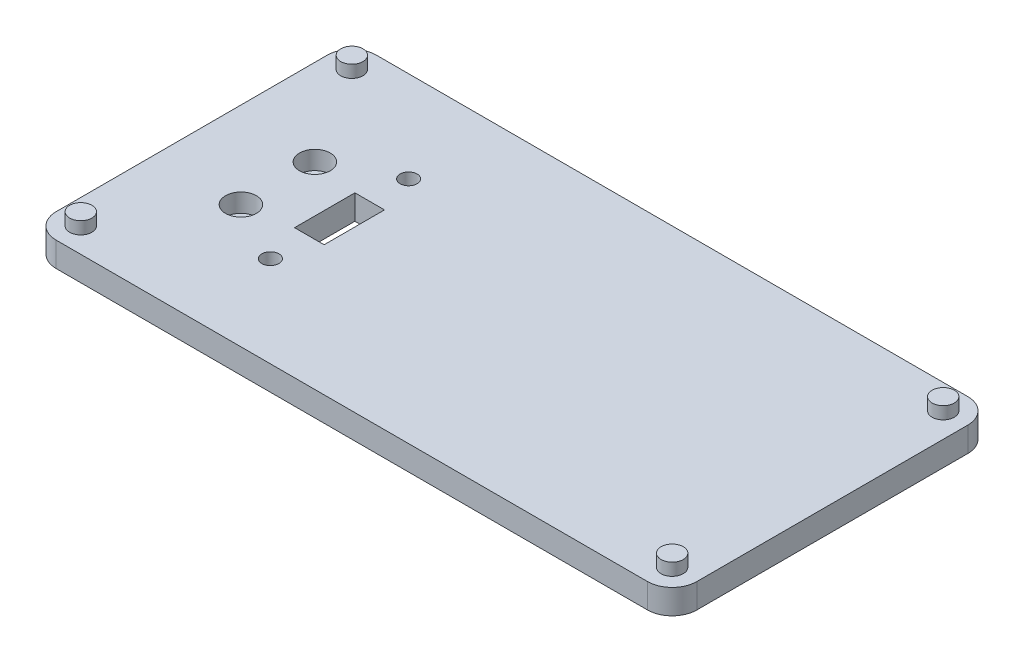
SolidWorks part; units mm, degrees
ref_plane "Front Plane" through (0, 0, 0) normal (0, 0, 1) x (1, 0, 0)
ref_plane "Top Plane" through (0, 0, 0) normal (0, 1, 0) x (1, 0, 0)
ref_plane "Right Plane" through (0, 0, 0) normal (1, 0, 0) x (0, 0, -1)
sketch "Sketch1" plane through (0, 0, 0) normal (0, 1, 0) x (1, 0, 0)
  line L1 (0, 0) -> (121.92, 0)
  line L2 (0, 0) -> (0, 66.04)
  line L3 (0, 66.04) -> (121.92, 66.04)
  line L4 (121.92, 0) -> (121.92, 66.04)
  dimension "D1" = 121.92
  dimension "D2" = 66.04
extrude "Boss-Extrude1" add sketch "Sketch1" along normal blind 5.08
fillet "Fillet1" radius 5.08 4 edges at (0, 2.54, -66.04) (121.92, 2.54, -66.04) (121.92, 2.54, 0) (0, 2.54, 0)
sketch "Sketch2" plane through (0, 5.08, 0) normal (0, 1, 0) x (1, 0, 0)
  line L0 (30.48, 39.243) -> (30.48, 26.797) construction
  line L1 (27.432, 39.243) -> (33.528, 39.243)
  line L2 (27.432, 39.243) -> (27.432, 26.797)
  line L3 (27.432, 26.797) -> (33.528, 26.797)
  line L4 (33.528, 39.243) -> (33.528, 26.797)
  line L5 (0, 60.96) -> (0, 5.08) construction
  line L6 (27.432, 33.02) -> (33.528, 33.02) construction
  circle A2 centre (30.48, 47.2694) radius 1.7526
  circle A3 centre (30.48, 18.7706) radius 1.7526
  dimension "D4" = 14.2494
  dimension "D2" = 3.5052
  dimension "D1" = 6.096
  dimension "D3" = 12.446
  dimension "D5" = 27.94
  dimension "D6" = 30.48
sketch "Sketch3" plane through (0, 5.08, 0) normal (0, 1, 0) x (1, 0, 0)
  line L0 (116.84, 66.04) -> (5.08, 66.04) construction
  line L1 (5.08, 0) -> (116.84, 0) construction
  line L2 (0, 60.96) -> (0, 5.08) construction
  circle A0 centre (17.78, 40.64) radius 3.175
  circle A1 centre (17.78, 25.4) radius 3.175
  dimension "D1" = 6.35
  dimension "D2" = 6.35
  dimension "D3" = 25.4
  dimension "D4" = 25.4
  dimension "D5" = 17.78
extrude "Cut-Extrude2" cut sketch "Sketch2" against normal up to next
extrude "Cut-Extrude3" cut sketch "Sketch3" against normal blind 3.81
sketch "Sketch4" plane through (0, 1.27, 0) normal (0, 1, 0) x (1, 0, 0)
  circle A0 centre (17.78, 40.64) radius 1.9812
  circle A1 centre (17.78, 25.4) radius 1.9812
  dimension "D1" = 3.9624
  dimension "D2" = 3.9624
extrude "Cut-Extrude4" cut sketch "Sketch4" against normal up to next
sketch "Sketch5" plane through (0, 5.08, 0) normal (0, 1, 0) x (1, 0, 0)
  line L0 (116.84, 66.04) -> (5.08, 66.04) construction
  line L1 (0, 60.96) -> (0, 5.08) construction
  line L2 (66.04, 66.04) -> (66.04, 0) construction
  line L4 (5.08, 0) -> (116.84, 0) construction
  line L6 (0, 33.02) -> (121.92, 33.02) construction
  line L7 (121.92, 5.08) -> (121.92, 60.96) construction
  circle A0 centre (5.08, 60.96) radius 2.286
  circle A4 centre (127, 60.96) radius 2.286
  circle A5 centre (127, 5.08) radius 2.286
  circle A6 centre (5.08, 5.08) radius 2.286
  dimension "D1" = 4.572
  dimension "D2" = 5.08
  dimension "D3" = 5.08
  dimension "D4" = 66.04
sketch "Sketch8" plane through (0, 0, 0) normal (0, -1, 0) x (1, 0, 0)
  line L0 (116.84, -66.04) -> (5.08, -66.04) construction
  line L1 (116.84, 0) -> (132.08, 0)
  line L2 (116.84, 0) -> (116.84, -66.04)
  line L3 (116.84, -66.04) -> (132.08, -66.04)
  line L4 (132.08, 0) -> (132.08, -66.04)
  dimension "D1" = 15.24
extrude "Boss-Extrude2" add sketch "Sketch8" against normal blind 5.08
fillet "Fillet4" radius 5.08 2 edges at (132.08, 2.54, 0) (132.08, 2.54, -66.04)
extrude "Boss-Extrude3" add sketch "Sketch5" along normal blind 2.54
